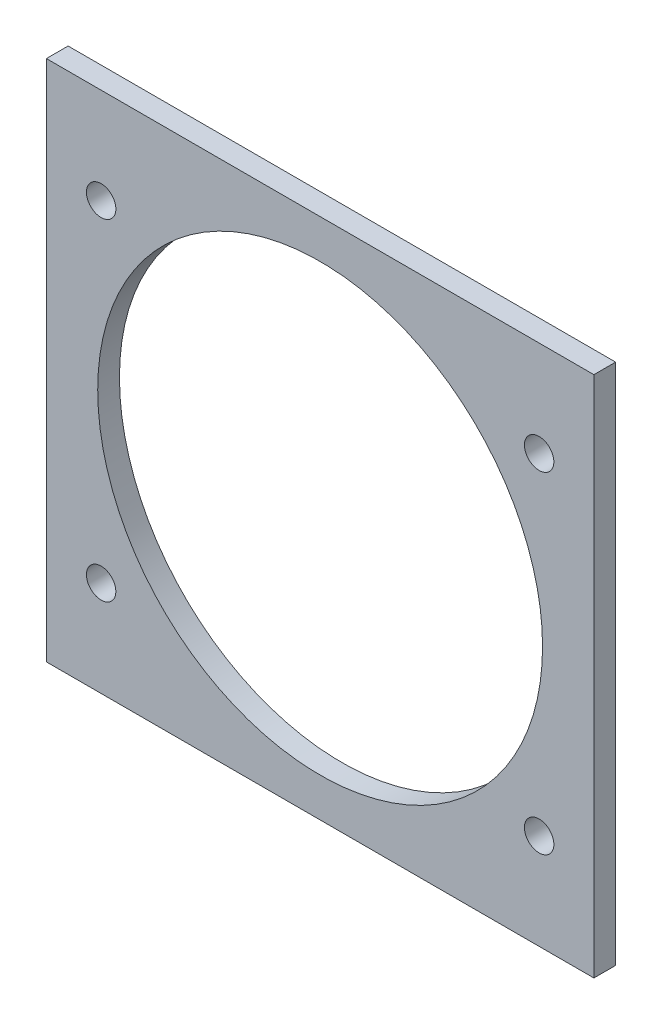
SolidWorks part; units mm, degrees
ref_plane "Front Plane" through (0, 0, 0) normal (0, 0, 1) x (1, 0, 0)
ref_plane "Top Plane" through (0, 0, 0) normal (0, 1, 0) x (1, 0, 0)
ref_plane "Right Plane" through (0, 0, 0) normal (1, 0, 0) x (0, 0, -1)
sketch "Sketch1" plane through (0, 0, 0) normal (0, 0, 1) x (1, 0, 0)
  line L0 (0, 38.175) -> (0, -38.175) construction
  line L1 (-40, -38.175) -> (40, -38.175)
  line L2 (-40, -38.175) -> (-40, 38.175)
  line L3 (-40, 38.175) -> (40, 38.175)
  line L4 (40, -38.175) -> (40, 38.175)
  line L5 (-40, -38.175) -> (40, 38.175) construction
  line L6 (-40, 38.175) -> (40, -38.175) construction
  line L7 (-40, 0) -> (40, 0) construction
  circle A10 centre (0, 0) radius 20 construction
  circle A14 centre (0, 0) radius 32.5
  circle A16 centre (-32, 24.2) radius 2.15
  circle A17 centre (-32, -24.2) radius 2.15
  circle A18 centre (32, -24.2) radius 2.15
  circle A19 centre (32, 24.2) radius 2.15
  point P0 (0, 0)
  point P52 (0, 0)
  dimension "D4" = 13.975
  dimension "D7" = 40
  dimension "D11" = 65
  dimension "D3" = 4.3
  dimension "D1" = 76.35
  dimension "D2" = 80
  dimension "D5" = 8
extrude "Boss-Extrude1" add sketch "Sketch1" along normal blind 3.175
